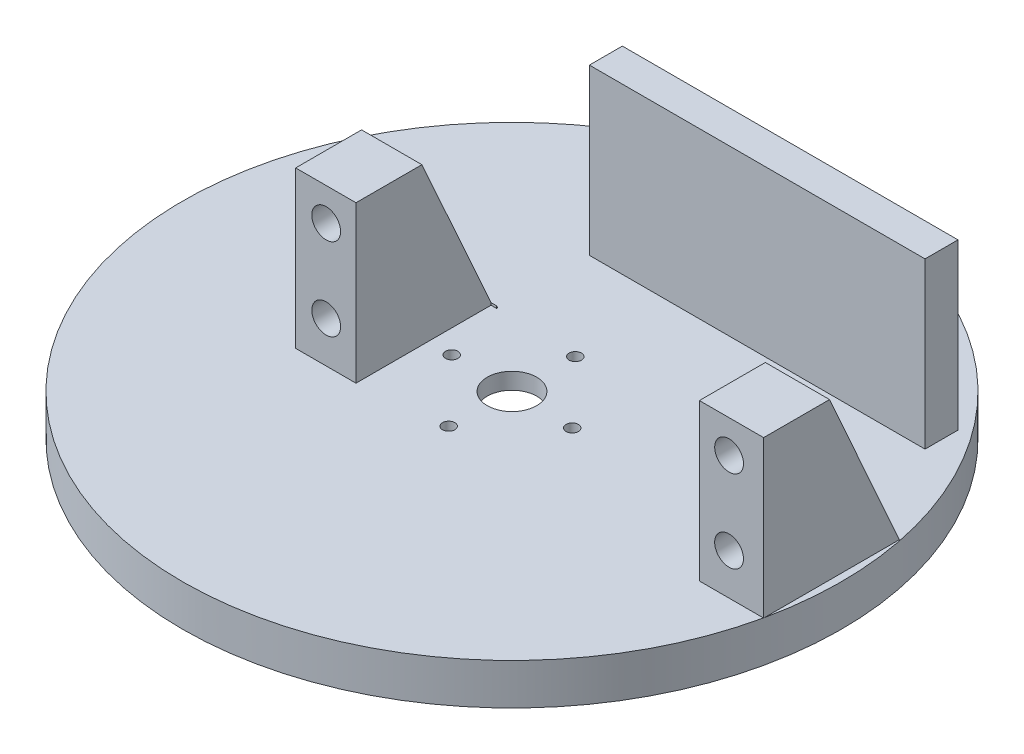
SolidWorks part; units mm, degrees
ref_plane "Vorne" through (0, 0, 0) normal (0, 0, 1) x (1, 0, 0)
ref_plane "Oben" through (0, 0, 0) normal (0, 1, 0) x (1, 0, 0)
ref_plane "Rechts" through (0, 0, 0) normal (1, 0, 0) x (0, 0, -1)
sketch "Skizze1" plane through (0, 0, 0) normal (0, 1, 0) x (1, 0, 0)
  circle A0 centre (0, 0) radius 40
  dimension "D1" = 80
extrude "Aufsatz-Linear austragen1" add sketch "Skizze1" along normal blind 5
sketch "Skizze2" plane through (0, 0, 0) normal (0, -1, 0) x (1, 0, 0)
  circle A0 centre (0, 0) radius 10.75
  dimension "D1" = 21.5
extrude "Schnitt-Linear austragen1" cut sketch "Skizze2" against normal blind 3
sketch "Skizze3" plane through (0, 0, 0) normal (0, -1, 0) x (1, 0, 0)
  circle A0 centre (0, 0) radius 3
  circle A1 centre (-0.186, 7.4977) radius 0.75
  circle A2 centre (7.4977, 0.186) radius 0.75
  circle A3 centre (0.186, -7.4977) radius 0.75
  circle A4 centre (-7.4977, -0.186) radius 0.75
extrude "Schnitt-Linear austragen2" cut sketch "Skizze3" against normal blind 13
sketch "Skizze4" plane through (0, 5, 0) normal (0, 1, 0) x (1, 0, 0)
  line L1 (-9.6495, -8.6042) -> (-17.6495, -8.6042)
  line L2 (-9.6495, -8.6042) -> (-9.6495, -0.6042)
  line L3 (-9.6495, -0.6042) -> (-17.6495, -0.6042)
  line L4 (-17.6495, -8.6042) -> (-17.6495, -0.6042)
  line L5 (31.0988, -8.555) -> (39.0988, -8.555)
  line L6 (31.0988, -8.555) -> (31.0988, -0.555)
  line L7 (31.0988, -0.555) -> (39.0988, -0.555)
  line L8 (39.0988, -8.555) -> (39.0988, -0.555)
  dimension "D1" = 8
  dimension "D2" = 8
  dimension "D3" = 8
  dimension "D4" = 8
extrude "Aufsatz-Linear austragen2" add sketch "Skizze4" along normal blind 18.97
sketch "Skizze5" plane through (39.0988, 0, 0) normal (1, 0, 0) x (0, 0, -1)
  line L0 (-0.555, 23.97) -> (7.9115, 5)
  line L1 (40, 5) -> (-40, 5) construction
  line L2 (7.9115, 5) -> (-0.555, 5)
  line L3 (-0.555, 5) -> (-0.555, 23.97)
extrude "Aufsatz-Linear austragen3" add sketch "Skizze5" against normal blind 8
sketch "Skizze6" plane through (-17.6495, 0, 0) normal (-1, 0, 0) x (0, 0, 1)
  line L0 (0.6042, 23.97) -> (-7.9115, 5)
  line L1 (-7.9115, 5) -> (0.6042, 5)
  line L3 (0.6042, 5) -> (0.6042, 23.97)
extrude "Aufsatz-Linear austragen4" add sketch "Skizze6" against normal blind 8
sketch "Skizze7" plane through (0, 0, 8.6042) normal (0, 0, 1) x (1, 0, 0)
  line L0 (-17.6495, 23.97) -> (-17.6495, 5) construction
  line L1 (39.0988, 23.97) -> (39.0988, 5) construction
  line L2 (-17.6495, 5) -> (-9.6495, 5) construction
  line L3 (40, 5) -> (-40, 5) construction
  circle A4 centre (-13.9442, 20) radius 1.75
  circle A5 centre (-13.9442, 10) radius 1.75
  circle A6 centre (34.9042, 10) radius 1.75
  circle A7 centre (34.9088, 20) radius 1.75
  dimension "D1" = 3.7054
  dimension "D2" = 3.7054
  dimension "D3" = 4.19
  dimension "D4" = 4.1946
  dimension "D5" = 5
  dimension "D6" = 15
  dimension "D7" = 5
  dimension "D8" = 15
  dimension "D9" = 3.5
  dimension "D10" = 3.5
  dimension "D11" = 3.5
  dimension "D12" = 3.5
extrude "Schnitt-Linear austragen3" cut sketch "Skizze7" against normal blind 33.27
sketch "Skizze9" plane through (0, 5, 0) normal (0, 1, 0) x (1, 0, 0)
  line L1 (-9.6012, 18.9983) -> (31.1368, 18.9983)
  line L2 (-9.6012, 18.9983) -> (-9.6012, 22.9983)
  line L3 (-9.6012, 22.9983) -> (31.1368, 22.9983)
  line L4 (31.1368, 18.9983) -> (31.1368, 22.9983)
  dimension "D1" = 4
extrude "Aufsatz-Linear austragen5" add sketch "Skizze9" along normal blind 20
sketch "Skizze10" plane through (0, 0, -22.9983) normal (0, 0, -1) x (-1, 0, 0)
  circle A1 centre (0.0442, 15) radius 3
  dimension "D1" = 6
extrude "Aufsatz-Linear austragen6" add sketch "Skizze10" along normal blind 4
sketch "Skizze11" plane through (0, 0, 8.6042) normal (0, 0, 1) x (1, 0, 0)
  line L1 (-9.6012, 5) -> (-10.3286, 5)
  line L2 (-9.6012, 5) -> (-9.6012, 24.15)
  line L3 (-9.6012, 24.15) -> (-10.3286, 24.15)
  line L4 (-10.3286, 5) -> (-10.3286, 24.15)
  line L5 (31.0988, 5) -> (31.3051, 5)
  line L6 (31.0988, 5) -> (31.0988, 24.15)
  line L7 (31.0988, 24.15) -> (31.3051, 24.15)
  line L8 (31.3051, 5) -> (31.3051, 24.15)
extrude "Schnitt-Linear austragen4" cut sketch "Skizze11" against normal blind 16.39
